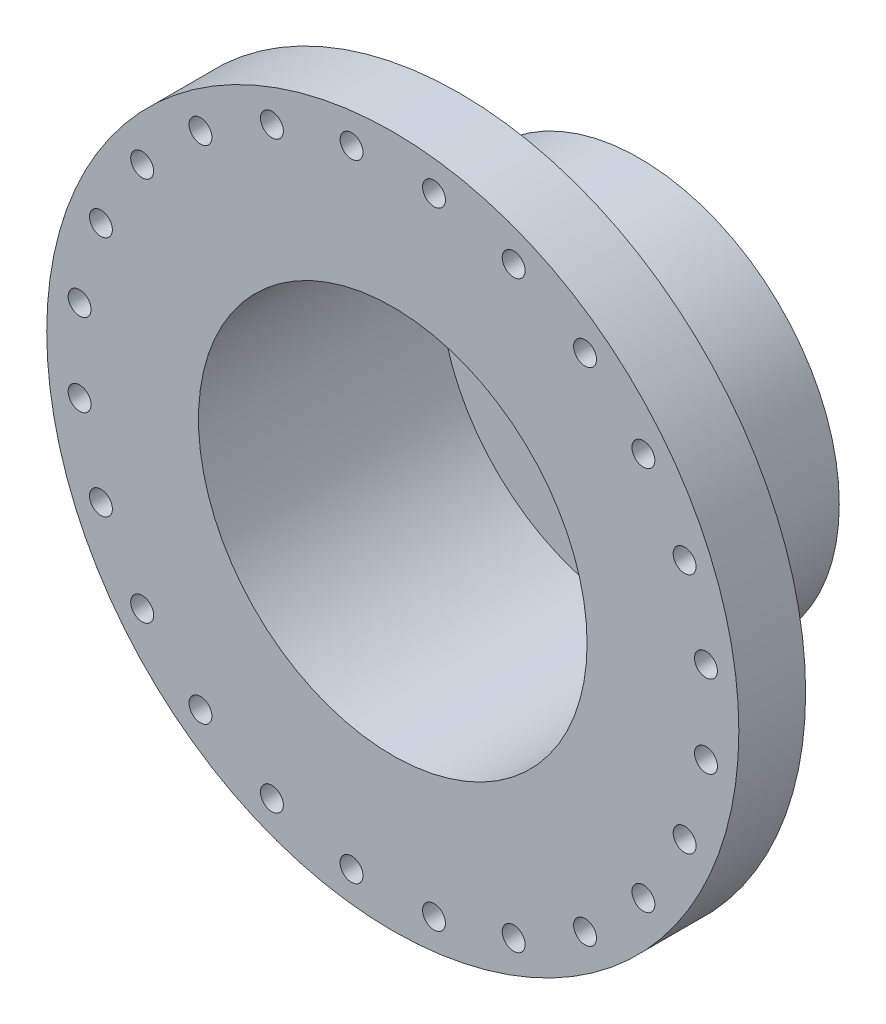
SolidWorks part; units mm, degrees
ref_plane "Front Plane" through (0, 0, 0) normal (0, 0, 1) x (1, 0, 0)
ref_plane "Top Plane" through (0, 0, 0) normal (0, 1, 0) x (1, 0, 0)
ref_plane "Right Plane" through (0, 0, 0) normal (1, 0, 0) x (0, 0, -1)
sketch "Sketch1" plane through (0, 0, 0) normal (0, 0, 1) x (1, 0, 0)
  circle A0 centre (0, 0) radius 73.3072
  circle A1 centre (0, 0) radius 71.3072
  dimension "D1" = 2
  dimension "D2" = 142.6144
extrude "Extrude1" add sketch "Sketch1" against normal blind 66.04
sketch "Sketch2" plane through (0, 0, 0) normal (0, 0, 1) x (1, 0, 0)
  circle A0 centre (0, 0) radius 71.3072
  circle A1 centre (0, 0) radius 127
  circle A2 centre (0, 0) radius 71.3072 construction
extrude "Extrude2" add sketch "Sketch2" along normal blind 24.511
sketch "Sketch3" plane through (0, 0, 24.511) normal (0, 0, 1) x (1, 0, 0)
  circle A0 centre (15.1313, -114.9338) radius 4.2
extrude "Cut-Extrude1" cut sketch "Sketch3" against normal up to next
pattern_circular "CirPattern1" count 24 over 360 about axis through (0, 0, 0) along (0, 0, 1) of "Cut-Extrude1"
sketch "Sketch4" plane through (0, 0, -66.04) normal (0, 0, -1) x (-1, 0, 0)
  circle A0 centre (0, 0) radius 73.3072
  circle A1 centre (0, 0) radius 25.4
  circle A2 centre (0, 0) radius 73.3072 construction
  dimension "D1" = 50.8
extrude "Extrude3" add sketch "Sketch4" against normal blind 2
sketch "Sketch8" plane through (0, 0, -66.04) normal (0, 0, -1) x (-1, 0, 0)
  circle A0 centre (0, 0) radius 29.21
  circle A1 centre (0, 0) radius 25.4
  dimension "D1" = 58.42
extrude "Extrude5" add sketch "Sketch8" against normal blind 5
sketch "Sketch9" plane through (0, 0, 0) normal (0, 1, 0) x (1, 0, 0)
  line L0 (0, 0) -> (0, 96.2422) construction
  line L1 (-29.1457, 61.04) -> (-25.4, 66.04)
  line L2 (-29.21, 61.04) -> (29.21, 61.04) construction
  line L3 (73.3072, 66.04) -> (-73.3072, 66.04) construction
  line L4 (25.4, 66.04) -> (-25.4, 66.04) construction
  line L5 (-25.4, 66.04) -> (-25.4, 61.04)
  line L6 (-25.4, 61.04) -> (25.4, 61.04) construction
  line L7 (-25.4, 61.04) -> (-29.1457, 61.04)
revolve "Cut-Revolve1" cut sketch "Sketch9" angle 360 about L0
